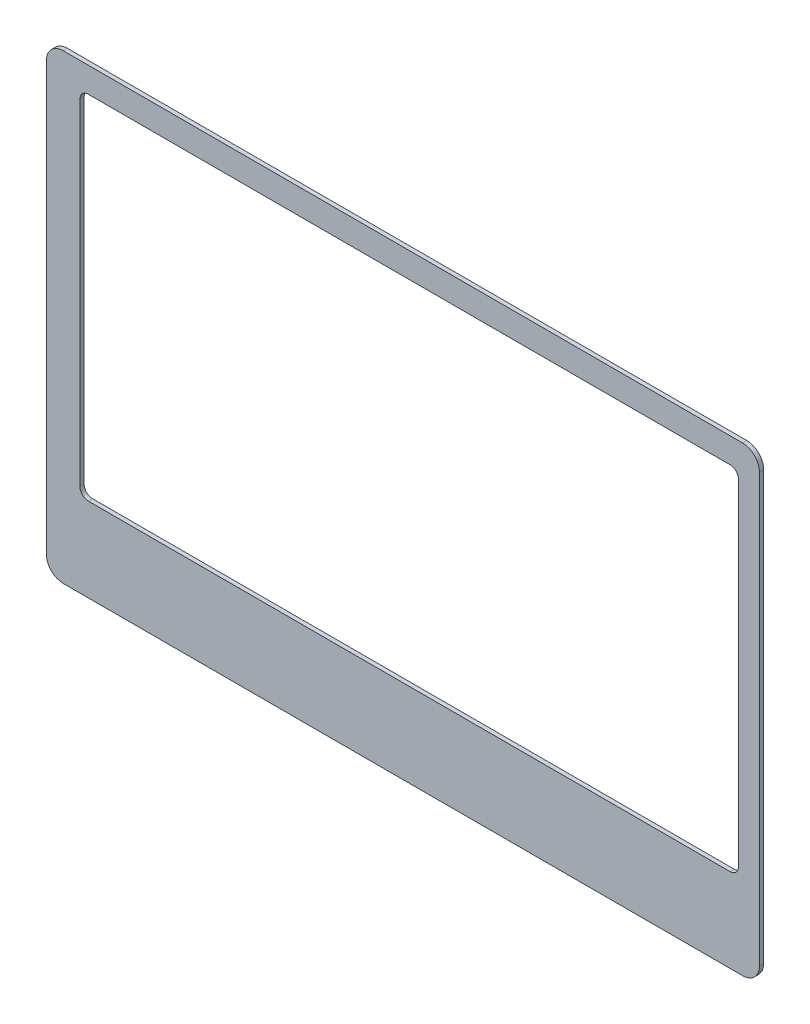
SolidWorks part; units mm, degrees
ref_plane "前视基准面" through (0, 0, 0) normal (0, 0, 1) x (1, 0, 0)
ref_plane "上视基准面" through (0, 0, 0) normal (0, 1, 0) x (1, 0, 0)
ref_plane "右视基准面" through (0, 0, 0) normal (1, 0, 0) x (0, 0, -1)
sketch "草图1" plane through (0, 0, 0) normal (0, 0, 1) x (1, 0, 0)
  line L1 (-42.5, 27.5) -> (42.5, 27.5)
  line L2 (-42.5, 27.5) -> (-42.5, -27.5)
  line L3 (-42.5, -27.5) -> (42.5, -27.5)
  line L4 (42.5, 27.5) -> (42.5, -27.5)
  line L5 (-42.5, 27.5) -> (42.5, -27.5) construction
  line L6 (-42.5, -27.5) -> (42.5, 27.5) construction
  point P0 (0, 0)
  dimension "D1" = 55
  dimension "D2" = 85
extrude "凸台-拉伸1" add sketch "草图1" along normal blind 0.5
sketch "草图2" plane through (0, 0, 0.5) normal (0, 0, 1) x (1, 0, 0)
  line L0 (42.5, -27.5) -> (42.5, 27.5) construction
  line L1 (-37.5, 24.5) -> (39, 24.5)
  line L2 (-38.5, 23.5) -> (-38.5, -16.5)
  line L3 (-37.5, -17.5) -> (39, -17.5)
  line L4 (40, 23.5) -> (40, -16.5)
  line L5 (-38.5, 24.5) -> (40, -17.5) construction
  line L6 (-38.5, -17.5) -> (40, 24.5) construction
  line L7 (-42.5, -27.5) -> (42.5, -27.5) construction
  arc A0 (-38.5, -16.5) -> (-37.5, -17.5) centre (-37.5, -16.5) ccw
  arc A1 (39, -17.5) -> (40, -16.5) centre (39, -16.5) ccw
  arc A2 (39, 24.5) -> (40, 23.5) centre (39, 23.5) cw
  arc A3 (-37.5, 24.5) -> (-38.5, 23.5) centre (-37.5, 23.5) ccw
  point P0 (0.75, 3.5)
  dimension "D5" = 1
  dimension "D1" = 42
  dimension "D2" = 78.5
  dimension "D3" = 2.5
  dimension "D4" = 10
extrude "切除-拉伸1" cut sketch "草图2" against normal up to next
fillet "圆角1" radius 2 4 edges at (42.5, -27.5, 0.25) (-42.5, -27.5, 0.25) (42.5, 27.5, 0.25) (-42.5, 27.5, 0.25)
